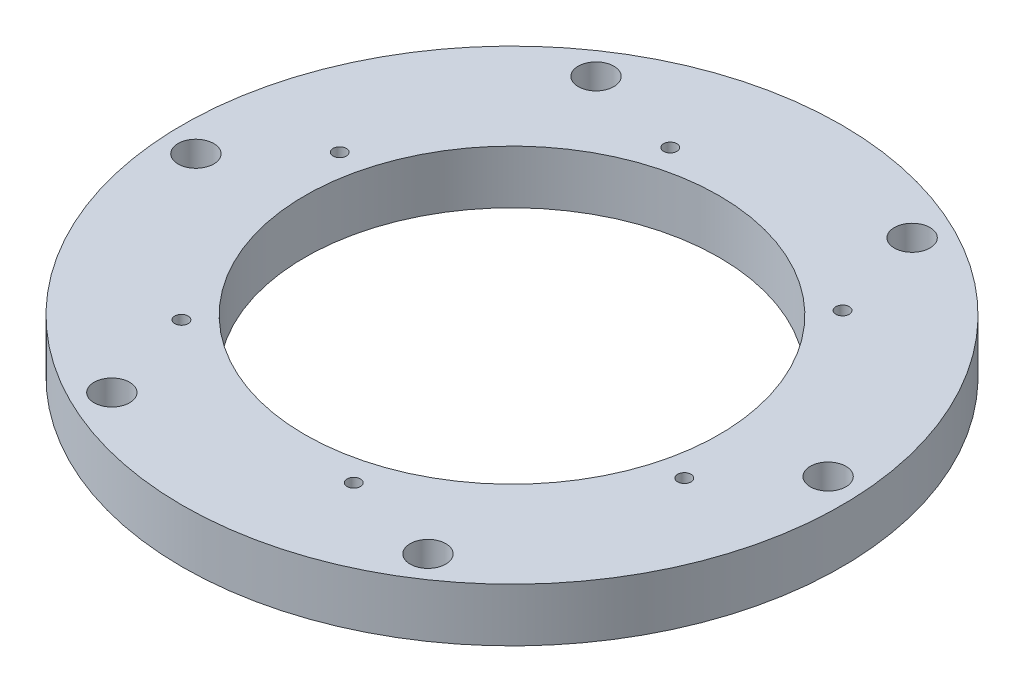
SolidWorks part; units mm, degrees
ref_plane "前视基准面" through (0, 0, 0) normal (0, 0, 1) x (1, 0, 0)
ref_plane "上视基准面" through (0, 0, 0) normal (0, 1, 0) x (1, 0, 0)
ref_plane "右视基准面" through (0, 0, 0) normal (1, 0, 0) x (0, 0, -1)
other "Configuration Table"
sketch "草图1" plane through (0, 0, 0) normal (0, 1, 0) x (1, 0, 0)
  circle A0 centre (0, 0) radius 74
  circle A1 centre (0, 0) radius 46.5
  circle A2 centre (36.1997, 38.0241) radius 1.5
  circle A3 centre (29.8814, 59.9675) radius 4
  circle A4 centre (66.8741, 4.1057) radius 4
  circle A5 centre (51.0297, -12.3378) radius 1.5
  circle A6 centre (36.9927, -55.8618) radius 4
  circle A7 centre (14.83, -50.3619) radius 1.5
  circle A8 centre (-29.8814, -59.9675) radius 4
  circle A9 centre (-36.1997, -38.0241) radius 1.5
  circle A10 centre (-66.8741, -4.1057) radius 4
  circle A11 centre (-51.0297, 12.3378) radius 1.5
  circle A12 centre (-36.9927, 55.8618) radius 4
  circle A13 centre (-14.83, 50.3619) radius 1.5
  point P31 (0, 0)
  dimension "D1" = 93
  dimension "D2" = 148
  dimension "D3" = 3
  dimension "D5" = 8
  dimension "D4" = 52.5
  dimension "D6" = 67
  dimension "D7" = 6
extrude "凸台-拉伸2" add sketch "草图1" along normal blind 12
